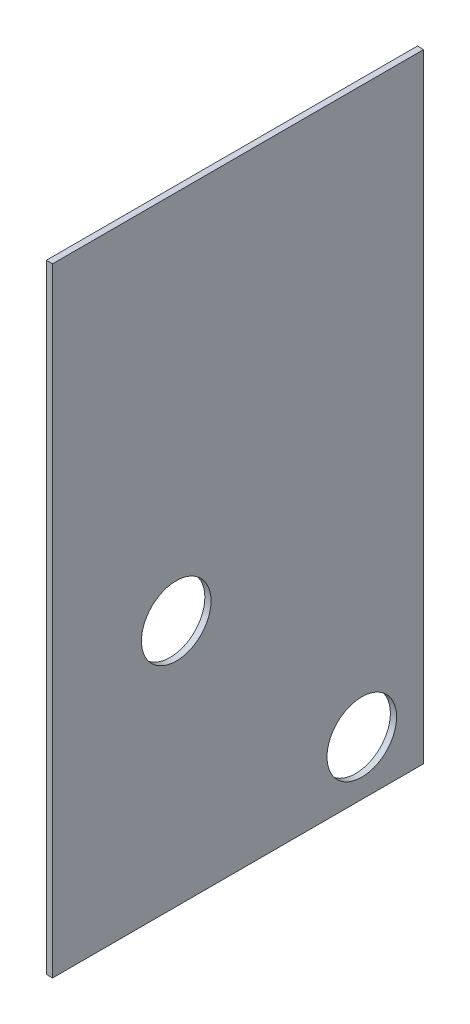
SolidWorks part; units mm, degrees
ref_plane "Front" through (0, 0, 0) normal (0, 0, 1) x (1, 0, 0)
ref_plane "Top" through (0, 0, 0) normal (0, 1, 0) x (1, 0, 0)
ref_plane "Right" through (0, 0, 0) normal (1, 0, 0) x (0, 0, -1)
sketch "Sketch1" plane through (0, 0, 0) normal (1, 0, 0) x (0, 0, -1)
  line L1 (-76.2, -127) -> (76.2, -127)
  line L2 (-76.2, -127) -> (-76.2, 127)
  line L3 (-76.2, 127) -> (76.2, 127)
  line L4 (76.2, -127) -> (76.2, 127)
  line L5 (-76.2, -127) -> (76.2, 127) construction
  line L6 (-76.2, 127) -> (76.2, -127) construction
  point P0 (0, 0)
  dimension "D1" = 254
  dimension "D2" = 152.4
extrude "Boss-Extrude1" add sketch "Sketch1" along normal mid plane 2.54
sketch "Sketch2" plane through (1.27, 0, 0) normal (1, 0, 0) x (0, 0, -1)
  line L0 (-76.2, -127) -> (76.2, -127) construction
  line L1 (-76.2, 127) -> (-76.2, -127) construction
  circle A0 centre (-25.4, -25.4) radius 14.2875
  dimension "D1" = 28.575
  dimension "D4" = 50.8
  dimension "D3" = 101.6
extrude "upper intake bearing hole" cut sketch "Sketch2" against normal up to surface (2.54 mm away) contours A0 up to face at (-1.27, 0, 0)
sketch "Sketch3" plane through (1.27, 0, 0) normal (1, 0, 0) x (0, 0, -1)
  line L0 (-76.2, 127) -> (-76.2, -127) construction
  line L1 (-76.2, -127) -> (76.2, -127) construction
  circle A0 centre (50.8, -104.775) radius 14.2875
  dimension "D1" = 28.575
  dimension "D2" = 127
  dimension "D3" = 22.225
extrude "lower intake bearing hole" cut sketch "Sketch3" against normal up to surface (2.54 mm away) up to face at (-1.27, -25.4, 39.6875)
